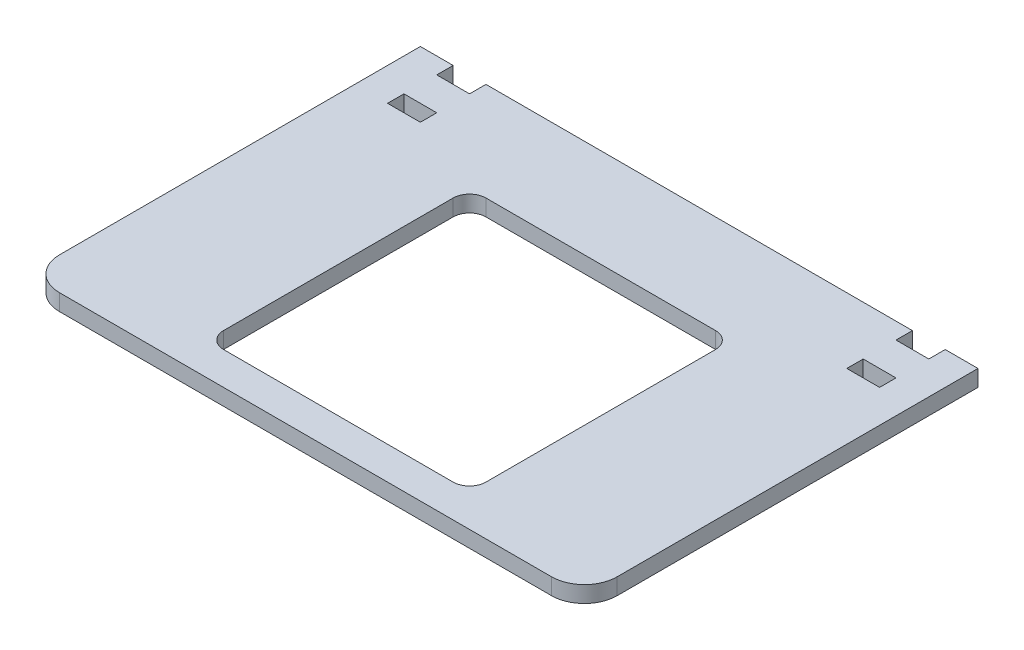
SolidWorks part; units mm, degrees
material "Pin"
ref_plane "Front" through (0, 0, 0) normal (0, 0, 1) x (1, 0, 0)
ref_plane "Top" through (0, 0, 0) normal (0, 1, 0) x (1, 0, 0)
ref_plane "Right" through (0, 0, 0) normal (1, 0, 0) x (0, 0, -1)
sketch "Esquisse2" plane through (0, 0, 0) normal (0, 1, 0) x (1, 0, 0)
  line L1 (-107.95, 76.2) -> (107.95, 76.2)
  line L2 (-107.95, 76.2) -> (-107.95, -76.2)
  line L3 (-107.95, -76.2) -> (107.95, -76.2)
  line L4 (107.95, 76.2) -> (107.95, -76.2)
  line L5 (-107.95, 76.2) -> (107.95, -76.2) construction
  line L6 (-107.95, -76.2) -> (107.95, 76.2) construction
  point P0 (0, 0)
  dimension "D1" = 215.9
  dimension "D2" = 152.4
extrude "Boss.-Extru.1" add sketch "Esquisse2" along normal blind 6.35
sketch "Esquisse3" plane through (0, 6.35, 0) normal (0, 1, 0) x (1, 0, 0)
  line L0 (-107.95, 76.2) -> (-107.95, -76.2) construction
  line L17 (-95.25, 76.2) -> (-82.55, 76.2)
  line L18 (-95.25, 76.2) -> (-95.25, 69.85)
  line L19 (-95.25, 69.85) -> (-82.55, 69.85)
  line L20 (-82.55, 76.2) -> (-82.55, 69.85)
  line L21 (-95.25, 76.2) -> (-82.55, 69.85) construction
  line L22 (-95.25, 69.85) -> (-82.55, 76.2) construction
  line L27 (0, 63.5) -> (-177.8, 63.5) construction
  line L28 (-95.25, 57.15) -> (-82.55, 57.15)
  line L42 (-95.25, 57.15) -> (-95.25, 50.8)
  line L43 (-95.25, 50.8) -> (-82.55, 50.8)
  line L44 (-82.55, 57.15) -> (-82.55, 50.8)
  line L45 (-95.25, 57.15) -> (-82.55, 50.8) construction
  line L46 (-95.25, 50.8) -> (-82.55, 57.15) construction
  line L67 (0, -50) -> (0, 50) construction
  line L72 (95.25, 50.8) -> (82.55, 57.15) construction
  line L73 (95.25, 57.15) -> (82.55, 50.8) construction
  line L78 (95.25, 69.85) -> (82.55, 76.2) construction
  line L79 (95.25, 76.2) -> (82.55, 69.85) construction
  line L96 (82.55, 57.15) -> (82.55, 50.8)
  line L97 (95.25, 50.8) -> (82.55, 50.8)
  line L98 (95.25, 57.15) -> (95.25, 50.8)
  line L99 (95.25, 57.15) -> (82.55, 57.15)
  line L100 (82.55, 76.2) -> (82.55, 69.85)
  line L101 (95.25, 69.85) -> (82.55, 69.85)
  line L102 (95.25, 76.2) -> (95.25, 69.85)
  line L103 (95.25, 76.2) -> (82.55, 76.2)
  line L104 (107.95, 76.2) -> (-107.95, 76.2) construction
  point P0 (-88.9, 73.025)
  point P5 (-88.9, 53.975)
  point P66 (88.9, 53.975)
  point P67 (88.9, 73.025)
  dimension "D1" = 6.35
  dimension "D2" = 12.7
  dimension "D3" = 12.7
  dimension "D4" = 6.35
  dimension "D5" = 12.7
  dimension "D6" = 12.7
  dimension "D7" = 6.35
  dimension "D15" = 12.7
extrude "Enlèv. mat.-Extru.1" cut sketch "Esquisse3" against normal through all and the other way through all
fillet "Congé1" radius 12.7 2 edges at (-107.95, 3.175, 76.2) (107.95, 3.175, 76.2)
sketch "Esquisse4" plane through (0, 6.35, 0) normal (0, 1, 0) x (1, 0, 0)
  line L1 (-44.45, 38.1) -> (44.45, 38.1)
  line L2 (-50.8, 31.75) -> (-50.8, -57.15)
  line L3 (-44.45, -63.5) -> (44.45, -63.5)
  line L4 (50.8, 31.75) -> (50.8, -57.15)
  line L5 (-50.8, 38.1) -> (50.8, -63.5) construction
  line L6 (-50.8, -63.5) -> (50.8, 38.1) construction
  line L8 (-95.25, -76.2) -> (95.25, -76.2) construction
  line L9 (107.95, -63.5) -> (107.95, 76.2) construction
  arc A0 (-50.8, -57.15) -> (-44.45, -63.5) centre (-44.45, -57.15) ccw
  arc A1 (-44.45, 38.1) -> (-50.8, 31.75) centre (-44.45, 31.75) ccw
  arc A2 (44.45, 38.1) -> (50.8, 31.75) centre (44.45, 31.75) cw
  arc A3 (44.45, -63.5) -> (50.8, -57.15) centre (44.45, -57.15) ccw
  point P0 (0, -12.7)
  dimension "D5" = 6.35
  dimension "D1" = 63.5
  dimension "D2" = 107.95
  dimension "D3" = 101.6
  dimension "D4" = 101.6
extrude "Enlèv. mat.-Extru.2" cut sketch "Esquisse4" against normal through all
